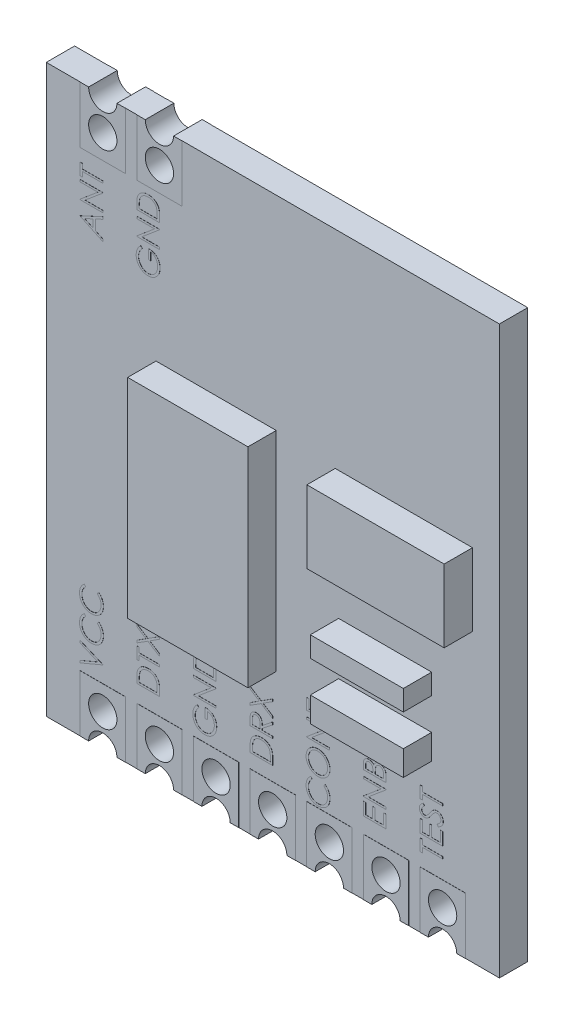
SolidWorks part; units mm, degrees
ref_plane "Ebene vorne" through (0, 0, 0) normal (0, 0, 1) x (1, 0, 0)
ref_plane "Ebene oben" through (0, 0, 0) normal (0, 1, 0) x (1, 0, 0)
ref_plane "Ebene rechts" through (0, 0, 0) normal (1, 0, 0) x (0, 0, -1)
sketch "Skizze1" plane through (0, 0, 0) normal (0, 0, 1) x (1, 0, 0)
  line L0 (0.5, -1.15) -> (1.5, -1.15)
  line L1 (-2, 18.85) -> (-0.5, 18.85)
  line L2 (-2, 18.85) -> (-2, -1.15)
  line L3 (-2, -1.15) -> (-0.5, -1.15)
  line L4 (14, 18.85) -> (14, -1.15)
  line L5 (2.5, -1.15) -> (3.5, -1.15)
  line L6 (4.5, -1.15) -> (5.5, -1.15)
  line L7 (6.5, -1.15) -> (7.5, -1.15)
  line L8 (8.5, -1.15) -> (9.5, -1.15)
  line L9 (10.5, -1.15) -> (11.5, -1.15)
  line L10 (12.5, -1.15) -> (14, -1.15)
  line L11 (0.5, 18.85) -> (1.5, 18.85)
  line L12 (2.5, 18.85) -> (14, 18.85)
  circle A0 centre (0, 0) radius 0.5
  circle A1 centre (2, 0) radius 0.5
  circle A2 centre (4, 0) radius 0.5
  circle A3 centre (6, 0) radius 0.5
  circle A4 centre (8, 0) radius 0.5
  circle A5 centre (10, 0) radius 0.5
  circle A6 centre (12, 0) radius 0.5
  arc A7 (0.5, -1.15) -> (-0.5, -1.15) centre (0, -1.15) ccw
  arc A8 (2.5, -1.15) -> (1.5, -1.15) centre (2, -1.15) ccw
  arc A9 (4.5, -1.15) -> (3.5, -1.15) centre (4, -1.15) ccw
  arc A10 (6.5, -1.15) -> (5.5, -1.15) centre (6, -1.15) ccw
  arc A11 (8.5, -1.15) -> (7.5, -1.15) centre (8, -1.15) ccw
  arc A12 (10.5, -1.15) -> (9.5, -1.15) centre (10, -1.15) ccw
  arc A13 (12.5, -1.15) -> (11.5, -1.15) centre (12, -1.15) ccw
  circle A14 centre (0, 17.7) radius 0.5
  circle A15 centre (2, 17.7) radius 0.5
  arc A16 (-0.5, 18.85) -> (0.5, 18.85) centre (0, 18.85) ccw
  arc A17 (1.5, 18.85) -> (2.5, 18.85) centre (2, 18.85) ccw
  point P47 (1.9067, 17.0962)
  point P48 (0, 0)
  point P49 (0, 0)
  point P53 (0, 0)
  dimension "D1" = 1
  dimension "D7" = 2
  dimension "D8" = 1.15
  dimension "D2" = 7
  dimension "D3" = 16
  dimension "D4" = 20
  dimension "D5" = 1.15
  dimension "D6" = 2
extrude "Aufsatz-Linear austragen1" add sketch "Skizze1" along normal blind 1
sketch "Skizze2" plane through (0, 0, 1) normal (0, 0, 1) x (1, 0, 0)
  line L1 (0.5, -1.15) -> (1.5, -1.15) construction
  line L2 (-0.8, 0.85) -> (0.8, 0.85)
  line L3 (-0.8, 0.85) -> (-0.8, -1.15)
  line L4 (-0.8, -1.15) -> (0.8, -1.15)
  line L5 (0.8, 0.85) -> (0.8, -1.15)
  line L6 (-0.8, 0.85) -> (0.8, -1.15) construction
  line L7 (-0.8, -1.15) -> (0.8, 0.85) construction
  point P0 (0, -0.15)
  point P5 (0.8717, -1.15)
  point P8 (0, 0)
  line M7 (-2, -1.15) -> (-0.5, -1.15)
  arc M8 (-0.5, -1.15) -> (0.5, -1.15) centre (0, -1.15) cw
  line M9 (0.5, -1.15) -> (1.5, -1.15)
  circle M24 centre (0, 0) radius 0.5
  dimension "D1" = 2
  dimension "D2" = 1.6
extrude "Aufsatz-Linear austragen2" add sketch "Skizze2" along normal blind 0.005 contours L5 L2 L3 M7 M8 M9 M24
pattern_linear "Lineares Muster1" count 7 spacing 2 along (1, 0, 0) of "Aufsatz-Linear austragen2"
sketch "Skizze3" plane through (0, 0, 1) normal (0, 0, 1) x (1, 0, 0)
  line L0 (-0.5, 18.85) -> (-2, 18.85) construction
  line L1 (0.8, 16.85) -> (-0.8, 16.85)
  line L2 (0.8, 16.85) -> (0.8, 18.85)
  line L3 (0.8, 18.85) -> (-0.8, 18.85)
  line L4 (-0.8, 16.85) -> (-0.8, 18.85)
  line L5 (0.8, 16.85) -> (-0.8, 18.85) construction
  line L6 (0.8, 18.85) -> (-0.8, 16.85) construction
  line L7 (1.5, 18.85) -> (0.5, 18.85) construction
  line L8 (2.8, 16.85) -> (1.2, 16.85)
  line L9 (2.8, 16.85) -> (2.8, 18.85)
  line L10 (2.8, 18.85) -> (1.2, 18.85)
  line L11 (1.2, 16.85) -> (1.2, 18.85)
  circle A0 centre (0, 17.7) radius 0.5 construction
  circle A1 centre (2, 17.7) radius 0.5 construction
  point P0 (0, 17.85)
  line M9 (14, 18.85) -> (2.5, 18.85)
  arc M10 (2.5, 18.85) -> (1.5, 18.85) centre (2, 18.85) cw
  line M11 (1.5, 18.85) -> (0.5, 18.85)
  arc M12 (0.5, 18.85) -> (-0.5, 18.85) centre (0, 18.85) cw
  line M13 (-0.5, 18.85) -> (-2, 18.85)
  circle M42 centre (0, 17.7) radius 0.5
  circle M43 centre (2, 17.7) radius 0.5
  dimension "D3" = 0.8
  dimension "D1" = 1.6
  dimension "D2" = 2
  dimension "D4" = 1.6
  dimension "D5" = 0.8
extrude "Aufsatz-Linear austragen3" add sketch "Skizze3" along normal blind 0.005 contours L11 L8 L9 M9 M10 M11 M43 | L4 L1 L2 M11 M12 M13 M42
ref_plane "Ebene1" through (0, 0, 0.5) normal (0, 0, 1) x (1, 0, 0)
mirror "Spiegeln1" about plane through (0, 0, 0.5) normal (0, 0, 1) of "Aufsatz-Linear austragen3", "Lineares Muster1", "Aufsatz-Linear austragen2"
sketch "Skizze4" plane through (0, 0, 1) normal (0, 0, 1) x (1, 0, 0)
  line L1 (1.8745, 11.6537) -> (6.1202, 11.6537)
  line L2 (1.8745, 11.6537) -> (1.8745, 4.2839)
  line L3 (1.8745, 4.2839) -> (6.1202, 4.2839)
  line L4 (6.1202, 11.6537) -> (6.1202, 4.2839)
  line L5 (1.8745, 11.6537) -> (6.1202, 4.2839) construction
  line L6 (1.8745, 4.2839) -> (6.1202, 11.6537) construction
  line L7 (8.2029, 8.9702) -> (13.0494, 8.9702)
  line L8 (8.2029, 8.9702) -> (8.2029, 11.5336)
  line L9 (8.2029, 11.5336) -> (13.0494, 11.5336)
  line L10 (13.0494, 8.9702) -> (13.0494, 11.5336)
  line L11 (8.2029, 8.9702) -> (13.0494, 11.5336) construction
  line L12 (8.2029, 11.5336) -> (13.0494, 8.9702) construction
  line L13 (8.3231, 7.0076) -> (11.6074, 7.0076)
  line L14 (8.3231, 7.0076) -> (8.3231, 6.2866)
  line L15 (8.3231, 6.2866) -> (11.6074, 6.2866)
  line L16 (11.6074, 7.0076) -> (11.6074, 6.2866)
  line L17 (8.3231, 7.0076) -> (11.6074, 6.2866) construction
  line L18 (8.3231, 6.2866) -> (11.6074, 7.0076) construction
  line L19 (8.3231, 5.1651) -> (11.6074, 5.1651)
  line L20 (8.3231, 5.1651) -> (8.3231, 4.2839)
  line L21 (8.3231, 4.2839) -> (11.6074, 4.2839)
  line L22 (11.6074, 5.1651) -> (11.6074, 4.2839)
  line L23 (8.3231, 5.1651) -> (11.6074, 4.2839) construction
  line L24 (8.3231, 4.2839) -> (11.6074, 5.1651) construction
  point P0 (3.9973, 7.9688)
  point P5 (9.9653, 4.7245)
  point P6 (10.6261, 10.2519)
  point P11 (9.9653, 6.6471)
  point P20 (9.9653, 6.6471)
extrude "Aufsatz-Linear austragen4" add sketch "Skizze4" along normal blind 1
sketch "Skizze5" plane through (0, 0, 1) normal (0, 0, 1) x (1, 0, 0)
  line L0 (0, 0.85) -> (0, 3.8172) construction
  line L1 (-0.8, 0.85) -> (0.8, 0.85) construction
  line L2 (2, 0.85) -> (2, 3.8172) construction
  line L5 (1.2, 0.85) -> (2.8, 0.85) construction
  line L6 (4, 0.85) -> (4, 3.8172) construction
  line L7 (3.2, 0.85) -> (4.8, 0.85) construction
  line L8 (6, 0.85) -> (6, 3.8172) construction
  line L9 (5.2, 0.85) -> (6.8, 0.85) construction
  line L10 (8, 0.85) -> (8, 3.8172) construction
  line L11 (7.2, 0.85) -> (8.8, 0.85) construction
  line L12 (10, 0.85) -> (10, 3.8172) construction
  line L13 (9.2, 0.85) -> (10.8, 0.85) construction
  line L14 (12, 0.85) -> (12, 3.8172) construction
  line L15 (11.2, 0.85) -> (12.8, 0.85) construction
  line L16 (0, 16.85) -> (0, 13.8828) construction
  line L17 (0.8, 16.85) -> (-0.8, 16.85) construction
  line L18 (2, 16.85) -> (2, 13.8828) construction
  line L19 (2.8, 16.85) -> (1.2, 16.85) construction
  text T0 "VCC" font "Century Gothic" height 0.8
  text T1 "DTX" font "Century Gothic" height 0.8
  text T2 "GND" font "Century Gothic" height 0.8
  text T3 "DRX" font "Century Gothic" height 0.8
  text T4 "CONF" font "Century Gothic" height 0.8
  text T5 "ENB" font "Century Gothic" height 0.8
  text T6 "TEST" font "Century Gothic" height 0.8
  text T7 "ANT" font "Century Gothic" height 0.8
  text T8 "GND" font "Century Gothic" height 0.8
  point P37 (0, 3.8172)
extrude "Aufsatz-Linear austragen5" add sketch "Skizze5" along normal blind 0.005
